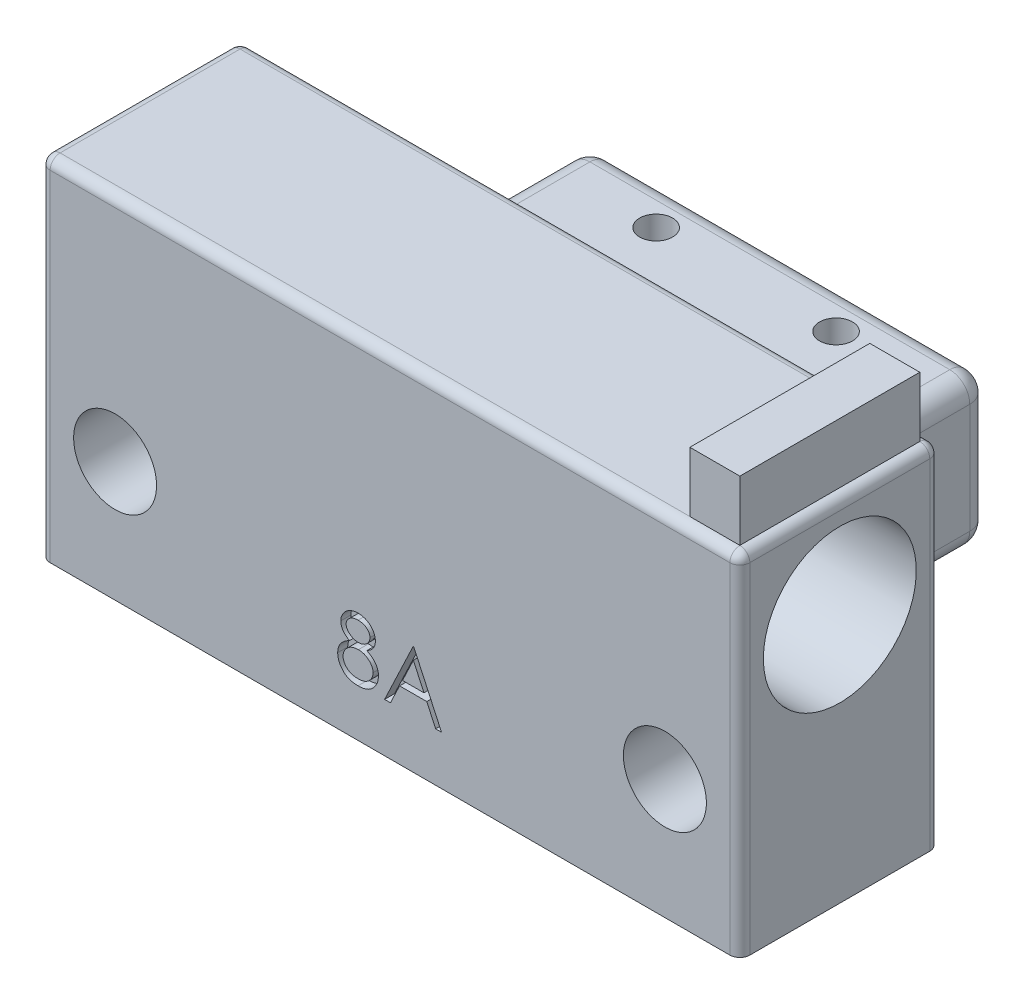
SolidWorks part; units mm, degrees
ref_plane "Alzado" through (0, 0, 0) normal (0, 0, 1) x (1, 0, 0)
ref_plane "Planta" through (0, 0, 0) normal (0, 1, 0) x (1, 0, 0)
ref_plane "Vista lateral" through (0, 0, 0) normal (1, 0, 0) x (0, 0, -1)
sketch "Croquis1" plane through (0, 0, 0) normal (0, 1, 0) x (1, 0, 0)
  line L1 (-35, -10) -> (35, -10)
  line L2 (-35, -10) -> (-35, 10)
  line L3 (-35, 10) -> (35, 10)
  line L4 (35, -10) -> (35, 10)
  line L5 (-35, -10) -> (35, 10) construction
  line L6 (-35, 10) -> (35, -10) construction
  point P0 (0, 0)
extrude "Saliente-Extruir1" add sketch "Croquis1" along normal blind 35
sketch "Croquis2" plane through (-35, 0, 0) normal (-1, 0, 0) x (0, 0, 1)
  line L0 (-10, 35) -> (0, 35) construction
  line L1 (-10, 35) -> (10, 35) construction
  line L2 (0, 35) -> (0, 25) construction
  circle A0 centre (0, 25) radius 7.65
extrude "Cortar-Extruir1" cut sketch "Croquis2" against normal through all
sketch "Croquis3" plane through (0, 0, -10) normal (0, 0, -1) x (-1, 0, 0)
  line L0 (-35, 0) -> (-27.5, 0) construction
  line L1 (-35, 0) -> (35, 0) construction
  line L2 (-27.5, 0) -> (-27.5, 12) construction
  line L3 (35, 0) -> (27.5, 0) construction
  line L4 (27.5, 0) -> (27.5, 12) construction
  circle A0 centre (-27.5, 12) radius 4.15
  circle A1 centre (27.5, 12) radius 4.15
extrude "Cortar-Extruir2" cut sketch "Croquis3" against normal through all
fillet "Redondeo1" radius 1 8 edges at (-35, 17.5, 10) (-35, 17.5, -10) (-35, 35, 0) (35, 17.5, 10) (0, 35, -10) (0, 35, 10) (35, 35, 0) (35, 17.5, -10)
sketch "Croquis5" plane through (0, 0, -10) normal (0, 0, -1) x (-1, 0, 0)
  line L0 (0, 0) -> (0, 8.7232) construction
  line L1 (-34, 0) -> (34, 0) construction
  line L3 (0, 8.7232) -> (0, 26) construction
  line L4 (0, 26) -> (20, 26) construction
  line L5 (20, 26) -> (20, 8.7232) construction
  line L6 (20, 8.7232) -> (-20, 8.7232) construction
  line L7 (-20, 8.7232) -> (-20, 23.7232) construction
  line L9 (20, 8.7232) -> (-20, 8.7232)
  line L10 (20, 8.7232) -> (20, 23.7232)
  line L11 (20, 23.7232) -> (-20, 23.7232)
  line L12 (-20, 8.7232) -> (-20, 23.7232)
  dimension "D1" = 8.7232
  dimension "D2" = 15
extrude "Saliente-Extruir3" add sketch "Croquis5" along normal blind 20
fillet "Redondeo3" radius 2 12 edges at (0, 8.7232, -10) (20, 8.7232, -20) (20, 16.2232, -10) (20, 23.7232, -20) (-20, 8.7232, -20) (0, 8.7232, -30) (20, 16.2232, -30) (0, 23.7232, -10) (-20, 23.7232, -20) (0, 23.7232, -30) (-20, 16.2232, -30) (-20, 16.2232, -10)
sketch "Croquis6" plane through (0, 23.7232, 0) normal (0, 1, 0) x (1, 0, 0)
  line L0 (18, 12) -> (18, 28) construction
  line L1 (-18, 12) -> (18, 12) construction
  line L2 (18, 28) -> (-18, 28) construction
  line L3 (0, 12) -> (0, 28) construction
  circle A0 centre (9, 14.375) radius 1.65
  circle A1 centre (9, 25.625) radius 1.65
  circle A2 centre (-9, 25.625) radius 1.65
  circle A3 centre (-9, 14.375) radius 1.65
  dimension "D1" = 9
  dimension "D2" = 9
  dimension "D3" = 2.375
  dimension "D4" = 2.375
extrude "Cortar-Extruir3" cut sketch "Croquis6" against normal up to next
sketch "Croquis7" plane through (0, 0, 10) normal (0, 0, 1) x (1, 0, 0)
  line L0 (-34, 4.8864) -> (34, 4.8864) construction
  line L1 (-34, 34) -> (-34, 0) construction
  line L2 (34, 0) -> (34, 34) construction
  text T0 "8A" font "Century Gothic" height 6
extrude "Cortar-Extruir4" cut sketch "Croquis7" against normal blind 1
sketch "Croquis8" plane through (0, 35, 0) normal (0, 1, 0) x (1, 0, 0)
  line L0 (34, 9) -> (-34, 9) construction
  line L1 (34, -9) -> (29, -9)
  line L2 (34, -9) -> (34, 9)
  line L3 (34, 9) -> (29, 9)
  line L4 (29, -9) -> (29, 9)
  dimension "D1" = 5
extrude "Saliente-Extruir4" add sketch "Croquis8" along normal blind 6
